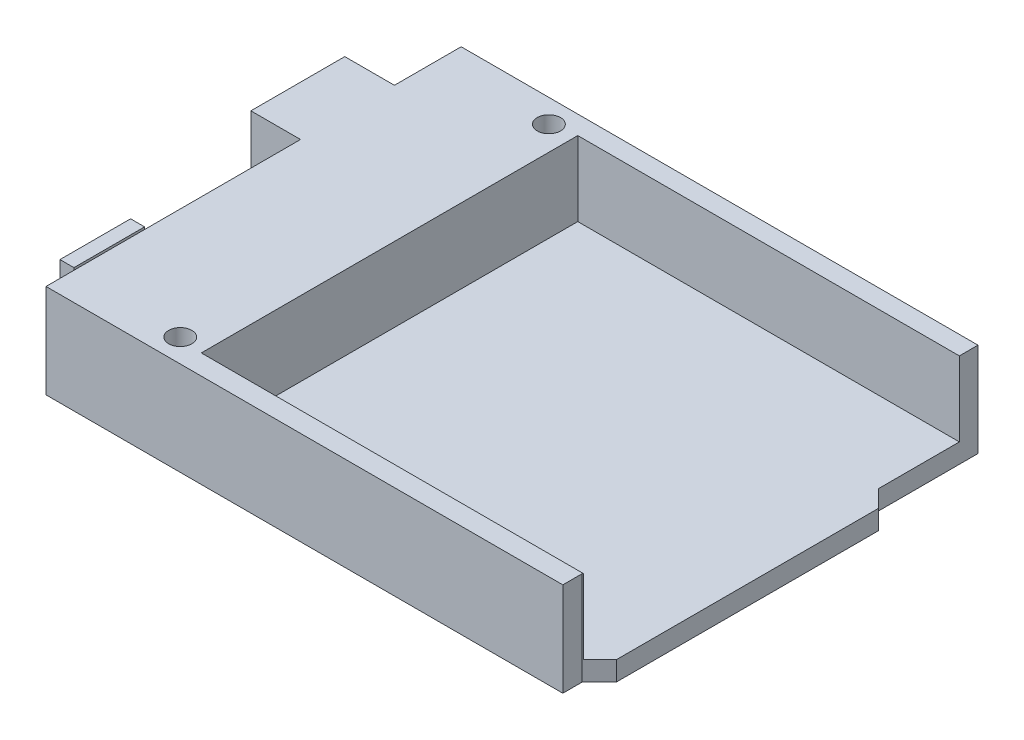
SolidWorks part; units mm, degrees
ref_plane "Front Plane" through (0, 0, 0) normal (0, 0, 1) x (1, 0, 0)
ref_plane "Top Plane" through (0, 0, 0) normal (0, 1, 0) x (1, 0, 0)
ref_plane "Right Plane" through (0, 0, 0) normal (1, 0, 0) x (0, 0, -1)
sketch "Sketch2" plane through (0, 0, 0) normal (0, 1, 0) x (1, 0, 0)
  line L1 (0, 0) -> (68.8, 0)
  line L2 (0, 0) -> (0, 53.5)
  line L3 (0, 53.5) -> (68.8, 53.5)
  line L4 (68.8, 0) -> (68.8, 53.5)
  dimension "D1" = 68.8
  dimension "D2" = 53.5
extrude "Boss-Extrude1" add sketch "Sketch2" along normal blind 12.1
sketch "Sketch3" plane through (0, 12.1, 0) normal (0, 1, 0) x (1, 0, 0)
  line L0 (66.6, 53.5) -> (66.6, 40.7)
  line L1 (68.8, 53.5) -> (0, 53.5) construction
  line L2 (66.6, 40.7) -> (68.8, 38.5)
  line L3 (68.8, 0) -> (68.8, 53.5) construction
  line L4 (68.8, 4.7) -> (66.6, 2.5)
  line L5 (66.6, 2.5) -> (66.6, 0)
  line L6 (0, 0) -> (68.8, 0) construction
  line L8 (0, 53.5) -> (68.8, 53.5)
  line L9 (0, 53.5) -> (0, 0)
  line L10 (0, 0) -> (68.8, 0)
  line L11 (68.8, 53.5) -> (68.8, 0)
  line M5 (0, 0) -> (68.8, 0)
  line M6 (68.8, 0) -> (68.8, 53.5)
  line M7 (68.8, 53.5) -> (0, 53.5)
  dimension "D1" = 45
  dimension "D2" = 2.2
  dimension "D3" = 2.5
  dimension "D4" = 12.8
extrude "Cut-Extrude1" cut sketch "Sketch3" against normal up to surface (12.1 mm away) contours L4 L5 M5 M6 | L0 L2 M6 M7 up to face at (34.4, 0, -26.75)
sketch "Sketch4" plane through (0, 0, 0) normal (-1, 0, 0) x (0, 0, 1)
  line L0 (-53.5, 12.1) -> (-53.5, 0) construction
  line L1 (-44.9, 12.1) -> (-32.8, 12.1)
  line L2 (-44.9, 12.1) -> (-44.9, 1.5)
  line L3 (-44.9, 1.5) -> (-32.8, 1.5)
  line L4 (-32.8, 12.1) -> (-32.8, 1.5)
  line L5 (-53.5, 0) -> (0, 0) construction
  dimension "D1" = 12.1
  dimension "D2" = 10.6
  dimension "D3" = 8.6
  dimension "D4" = 1.5
extrude "Boss-Extrude2" add sketch "Sketch4" along normal blind 6.4
sketch "Sketch5" plane through (0, 0, 0) normal (-1, 0, 0) x (0, 0, 1)
  line L0 (0, 12.1) -> (0, 0) construction
  line L1 (-12.7, 12.4) -> (-3.6, 12.4)
  line L2 (-12.7, 12.4) -> (-12.7, 1.5)
  line L3 (-12.7, 1.5) -> (-3.6, 1.5)
  line L4 (-3.6, 12.4) -> (-3.6, 1.5)
  line L5 (-44.9, 1.5) -> (-32.8, 1.5) construction
  dimension "D1" = 9.1
  dimension "D2" = 10.9
  dimension "D3" = 3.6
extrude "Boss-Extrude3" add sketch "Sketch5" along normal blind 1.8
sketch "Sketch7" plane through (0, 12.1, 0) normal (0, 1, 0) x (1, 0, 0)
  line L0 (0, 3.6) -> (0, 12.7) construction
  line L1 (0, 0) -> (66.6, 0) construction
  line L2 (66.6, 53.5) -> (0, 53.5) construction
  circle A0 centre (14.3, 50.5) radius 1.5
  circle A1 centre (14.3, 3) radius 1.5
  dimension "D1" = 3
  dimension "D2" = 14.3
  dimension "D3" = 3
  dimension "D4" = 3
extrude "Cut-Extrude2" cut sketch "Sketch7" against normal up to surface (12.1 mm away) up to face at (50.5, 0, -24.175)
sketch "Sketch8" plane through (0, 12.1, 0) normal (0, 1, 0) x (1, 0, 0)
  line L0 (66.6, 53.5) -> (0, 53.5) construction
  line L1 (17.425, 51.1) -> (83.9409, 51.1)
  line L2 (17.425, 51.1) -> (17.425, 2.5866)
  line L3 (17.425, 2.5866) -> (83.9409, 2.5866)
  line L4 (83.9409, 51.1) -> (83.9409, 2.5866)
  dimension "D1" = 2.4
extrude "Cut-Extrude3" cut sketch "Sketch8" against normal offset from surface (9.6 mm away) 2.5 up to face at (14.3, 0, -52)
